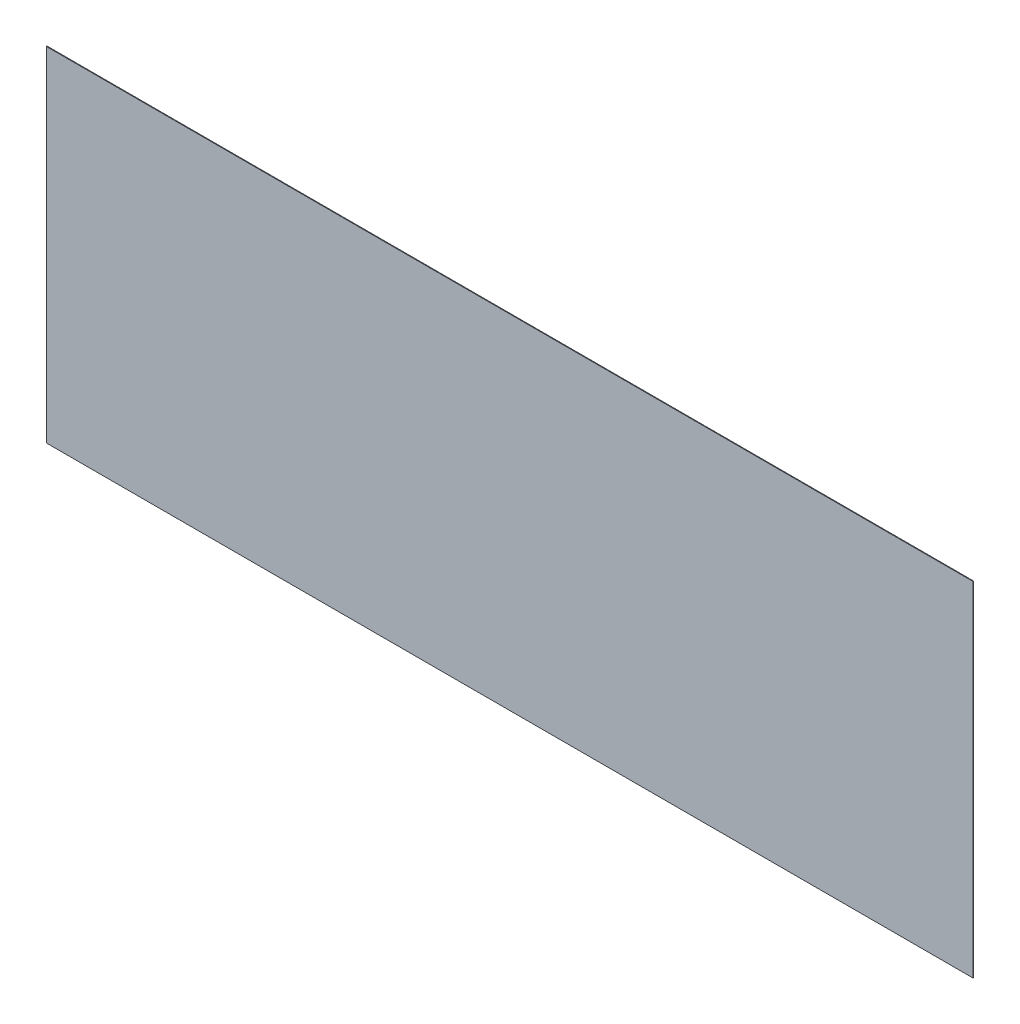
SolidWorks part; units mm, degrees
ref_plane "Front Plane" through (0, 0, 0) normal (0, 0, 1) x (1, 0, 0)
ref_plane "Top Plane" through (0, 0, 0) normal (0, 1, 0) x (1, 0, 0)
ref_plane "Right Plane" through (0, 0, 0) normal (1, 0, 0) x (0, 0, -1)
sketch "Sketch1" plane through (0, 0, 0) normal (0, 0, 1) x (1, 0, 0)
  line L1 (-137.5, 0) -> (137.5, 0)
  line L2 (-137.5, 0) -> (-137.5, 101.925)
  line L3 (-137.5, 101.925) -> (137.5, 101.925)
  line L4 (137.5, 0) -> (137.5, 101.925)
  line L5 (-137.5, 0) -> (137.5, 101.925) construction
  line L6 (-137.5, 101.925) -> (137.5, 0) construction
  point P0 (0, 50.9625)
  point P7 (0, 0)
  dimension "D1" = 275
  dimension "D2" = 101.925
extrude "Dimensions" add sketch "Sketch1" along normal mid plane 0.2
sketch "Right_view" plane through (0, 0, 0) normal (1, 0, 0) x (0, 0, -1)
  line L0 (113.8904, 203.4278) -> (1137.8904, 203.4278) construction
  line L1 (-105.4254, 36.1312) -> (-104.906, 19.1312)
  line L2 (-105.4254, 36.1312) -> (-105.4254, 2.3661) construction
  point P14 (-122.4576, 27.1029)
  dimension "D1" = 1.75
  dimension "D2" = 17
sketch "Front_view" plane through (0, 0, 0) normal (0, 0, 1) x (1, 0, 0)
  line L0 (-347.8413, -38.6566) -> (-347.8413, 985.3434) construction
  line L2 (0, 36.1312) -> (0, 19.1312) construction
  line L3 (0, 36.1312) -> (0, 19.1312)
sketch "Top_view" plane through (0, 0, 0) normal (0, 1, 0) x (1, 0, 0)
  line L0 (-353.5902, 134.1401) -> (-353.5902, 1158.1401) construction
sketch "Sections A-F" plane through (0, 0, 0) normal (0, 0, 1) x (1, 0, 0)
  line L0 (-24.8491, 90.6751) -> (111.8176, 90.6751) construction
ref_plane "A" through (0, -3.1843, 104.2242) normal (0, -0.0305, 0.9995) x (1, 0, 0)
ref_plane "B" through (0, 0, 101.7) normal (0, 0, 1) x (1, 0, 0)
ref_plane "C" through (0, 0, 81) normal (0, 0, 1) x (1, 0, 0)
ref_plane "D" through (0, 0, 67) normal (0, 0, 1) x (1, 0, 0)
ref_plane "E" through (0, 0, 46) normal (0, 0, 1) x (1, 0, 0)
ref_plane "F" through (0, 0, 34) normal (0, 0, 1) x (1, 0, 0)
ref_plane "G" through (0, 0, 11.6) normal (0, 0, 1) x (1, 0, 0)
ref_plane "H" through (0, 0, -22.5) normal (0, 0, 1) x (1, 0, 0)
ref_plane "J" through (0, 0, -57.5) normal (0, 0, 1) x (1, 0, 0)
ref_plane "K" through (0, 0, -93) normal (0, 0, 1) x (1, 0, 0)
ref_plane "L" through (0, 0, -106.8) normal (0, 0, 1) x (1, 0, 0)
sketch "Nose_sketch" plane through (0, 0, 0) normal (1, 0, 0) x (0, 0, -1)
  line L0 (-105.4254, 36.1312) -> (-104.906, 19.1312) construction
  line L1 (-105.4254, 36.1312) -> (-104.906, 19.1312) construction
  line L2 (-105.1657, 27.6312) -> (-122.4576, 27.1029) construction
  spline S0 degree 3 poles (-122.4576, 27.1029) (-121.0272, 30.9739) (-113.797, 34.4957) (-105.4254, 36.1312) knots 0 0 0 0 1 1 1 1
  point P0 (-105.4254, 36.1312)
  point P2 (-104.906, 19.1312)
sketch "A-F curve" plane through (0, 0, 0) normal (1, 0, 0) x (0, 0, -1)
  line L0 (-101.7, 87.5918) -> (-101.7, -87.5918) construction
  line L1 (-81, 95.462) -> (-81, -95.462) construction
  line L2 (-67, 101.2335) -> (-67, -101.2335) construction
  line L3 (-46, 98.6101) -> (-46, -98.6101) construction
  line L4 (-34, 99.1348) -> (-34, -99.1348) construction
  spline S0 degree 3 poles (-105.4254, 36.1312) (-97.9668, 39.2829) (-71.6052, 42.612) (-28.3902, 42.7499) knots 0 0 0 0 1 1 1 1
  point P0 (-105.4254, 36.1312)
  point P1 (-28.3902, 42.7499)
  point P5 (-101.7, 37.3268)
  point P6 (-34, 42.7134)
  point P9 (-67, 41.607)
  point P10 (-81, 40.5042)
  point P11 (-46, 42.502)
  point P16 (0, 0)
  point P21 (0, 0)
  point P22 (0, 0)
  point P23 (0, 0)
  point P24 (-46, 42.502)
sketch "H-J curve" plane through (0, 0, 0) normal (1, 0, 0) x (0, 0, -1)
  line L0 (22.5, 278.575) -> (22.5, -278.575) construction
  line L1 (57.5, 278.575) -> (57.5, -278.575) construction
  spline S0 degree 2 poles (22.5, 41.6479) (41.1937, 40.9469) (57.5, 39.5072) knots 0 0 0 1 1 1
  point P0 (22.5, 41.6479)
  point P1 (57.5, 39.5072)
sketch "J-L curve" plane through (0, 0, 0) normal (1, 0, 0) x (0, 0, -1)
  line L0 (106.8, 278.575) -> (106.8, -278.575) construction
  spline S0 degree 3 poles (57.5, 39.5072) (78.6177, 44.1237) (87.6019, 43.1159) (99.0659, 73.4822) (99.5301, 70.1255) (106.8, 70.4651) knots 0 0 0 0 0.333706 0.433706 1 1 1 1
  point P0 (57.5, 39.5072)
  point P1 (106.8, 70.4651)
sketch "B-G curve" plane through (0, 0, 0) normal (1, 0, 0) x (0, 0, -1)
  line L0 (-101.7, 87.5918) -> (-101.7, -87.5918) construction
  line L1 (-81, 95.462) -> (-81, -95.462) construction
  line L2 (-67, 101.2335) -> (-67, -101.2335) construction
  line L3 (-46, 98.6101) -> (-46, -98.6101) construction
  line L4 (-34, 99.1348) -> (-34, -99.1348) construction
  line L5 (-11.6, 95.462) -> (-11.6, -95.462) construction
  spline S0 degree 3 poles (-101.7, 15.0452) (-76.5379, 7.729) (-40.8594, 5.1442) (-11.6, 8.1082) knots 0 0 0 0 1 1 1 1
  point P0 (-104.906, 19.1312)
  point P1 (-11.6, 8.1082)
  point P3 (-101.7, 15.0452)
  point P6 (-67, 8.5301)
  point P7 (-46, 7.0604)
  point P10 (-81, 10.4378)
  point P15 (-34, 6.917)
  point P18 (0, 0)
sketch "G-J curve" plane through (0, 0, 0) normal (1, 0, 0) x (0, 0, -1)
  line L0 (57.5, 278.575) -> (57.5, -278.575) construction
  spline S0 degree 3 poles (-13.3541, 0.9062) (8.9964, -2.5515) (33.8203, 6.5708) (57.5, 16.3895) knots 0 0 0 0 1 1 1 1
  point P0 (-13.3541, 0.9062)
  point P1 (57.5, 16.3895)
sketch "Section_A" plane through (0, -3.1843, 104.2242) normal (0, -0.0305, 0.9995) x (1, 0, 0)
  line L4 (0, 37.3339) -> (0, 39.3339)
  line L5 (0, 24.3259) -> (0, 22.3259)
  line L8 (127.5, 10.0031) -> (127.5, 91.8805)
  line L9 (127.5, 91.8805) -> (-127.5, 91.8805)
  line L10 (-127.5, 91.8805) -> (-127.5, 10.0031)
  line L11 (-127.5, 10.0031) -> (127.5, 10.0031)
  line L12 (127.5, 10.0031) -> (127.5, 91.8805)
  line L13 (127.5, 91.8805) -> (-127.5, 91.8805)
  line L14 (-127.5, 91.8805) -> (-127.5, 10.0031)
  line L15 (-127.5, 10.0031) -> (127.5, 10.0031)
  arc A0 (0, 39.3339) -> (0, 22.3259) centre (0, 30.8299) cw
  arc A1 (0, 37.3339) -> (0, 24.3259) centre (0, 30.8299) cw
  point P0 (0, 39.3339)
  point P1 (0, 22.3259)
  dimension "D1" = 10
  dimension "D2" = 2
sketch "Section_B" plane through (0, 0, 101.7) normal (0, 0, 1) x (1, 0, 0)
  line L0 (0, 15.0452) -> (7.086, 15.0452) construction
  line L1 (0, 37.3268) -> (10.3034, 37.3268) construction
  spline S0 degree 3 poles (0, 37.3268) (9.1999, 37.3268) (12.4584, 26.5746) (5.154, 19.1921) knots 0 0 0 0 1 1 1 1
  spline S1 degree 3 poles (5.154, 19.1921) (5.0782, 16.3394) (4.1366, 14.9499) (0, 15.0452) knots 0 0 0 0 1 1 1 1
  point P0 (0, 37.3268)
  point P2 (0, 15.0452)
  point P4 (5.154, 19.1921)
sketch "Section_C" plane through (0, 0, 81) normal (0, 0, 1) x (1, 0, 0)
  line L0 (0, 0) -> (0, 10.4378) construction
  line L1 (0, 10.4378) -> (8.3914, 10.4378) construction
  line L2 (0, 40.5042) -> (15.8228, 40.5042) construction
  line L3 (10.5467, 16.1081) -> (10.5467, 12.1348) construction
  spline S0 degree 3 poles (0, 40.5042) (10.0564, 40.5042) (10.5467, 33.6527) (10.5467, 16.1081) knots 0 0 0 0 1 1 1 1
  spline S1 degree 3 poles (0, 10.4378) (5.9085, 10.4378) (10.5467, 13.8779) (10.5467, 16.1081) knots 0 0 0 0 1 1 1 1
  point P0 (0, 10.4378)
  point P3 (0, 40.5042)
  point P5 (0, 0)
  point P9 (10.5467, 16.1081)
sketch "Section_D" plane through (0, 0, 67) normal (0, 0, 1) x (1, 0, 0)
  line L0 (0, 41.607) -> (9.8218, 41.607) construction
  line L1 (0, 8.5301) -> (17.5822, 8.5301) construction
  spline S0 degree 3 poles (0, 8.5301) (9.7361, 8.5301) (10.9614, 11.177) (11.0999, 18.8243) (10.2953, 27.4621) (9.4639, 35.9597) (7.7456, 41.607) (0, 41.607) knots 0 0 0 0 0.417067 0.499389 0.787242 0.840901 1 1 1 1
  point P0 (0, 8.5301)
  point P2 (0, 41.607)
sketch "Section_E" plane through (0, 0, 46) normal (0, 0, 1) x (1, 0, 0)
  line L0 (0, 42.502) -> (8.9078, 42.502) construction
  line L1 (0, 7.0604) -> (16.6585, 7.0604) construction
  line L2 (13.3025, 9.1226) -> (13.3025, 17.5061)
  line L3 (11.2972, 19.5114) -> (11.2972, 36.1546) construction
  line L4 (13.3025, 17.5061) -> (9.1454, 17.5061) construction
  arc A0 (13.3025, 17.5061) -> (11.2972, 19.5114) centre (13.3025, 19.5114) cw
  spline S0 degree 2 poles (0, 7.0604) (2.0508, 7.0604) (13.3025, 9.1226) knots 0 0 0 1 1 1
  spline S1 degree 3 poles (0, 42.502) (10.8817, 42.502) (10.5558, 31.6861) (11.2972, 19.5114) knots 0 0 0 0 1 1 1 1
  point P0 (0, 42.502)
  point P2 (0, 7.0604)
sketch "Section_F" plane through (0, 0, 34) normal (0, 0, 1) x (1, 0, 0)
  line L0 (0, 42.7499) -> (11.4291, 42.7499) construction
  line L1 (0, 6.917) -> (14.7019, 6.917) construction
  line L3 (14.6809, 8.0929) -> (14.6809, 17.6757)
  line L4 (14.6809, 17.6757) -> (7.556, 17.6757) construction
  line L5 (11.547, 19.4226) -> (11.547, 36.2244) construction
  line L6 (14.6809, 17.6757) -> (13.2939, 17.6757)
  arc A0 (13.2939, 17.6757) -> (11.547, 19.4226) centre (13.2939, 19.4226) cw
  spline S0 degree 2 poles (0, 6.917) (5.0112, 6.917) (14.6809, 8.0929) knots 0 0 0 1 1 1
  spline S1 degree 3 poles (11.547, 19.4226) (11.547, 30.4057) (10.5058, 42.7499) (0, 42.7499) knots 0 0 0 0 1 1 1 1
  point P0 (0, 42.7134)
  point P2 (0, 6.917)
  point P12 (0, 0)
  point P14 (11.547, 19.4226)
